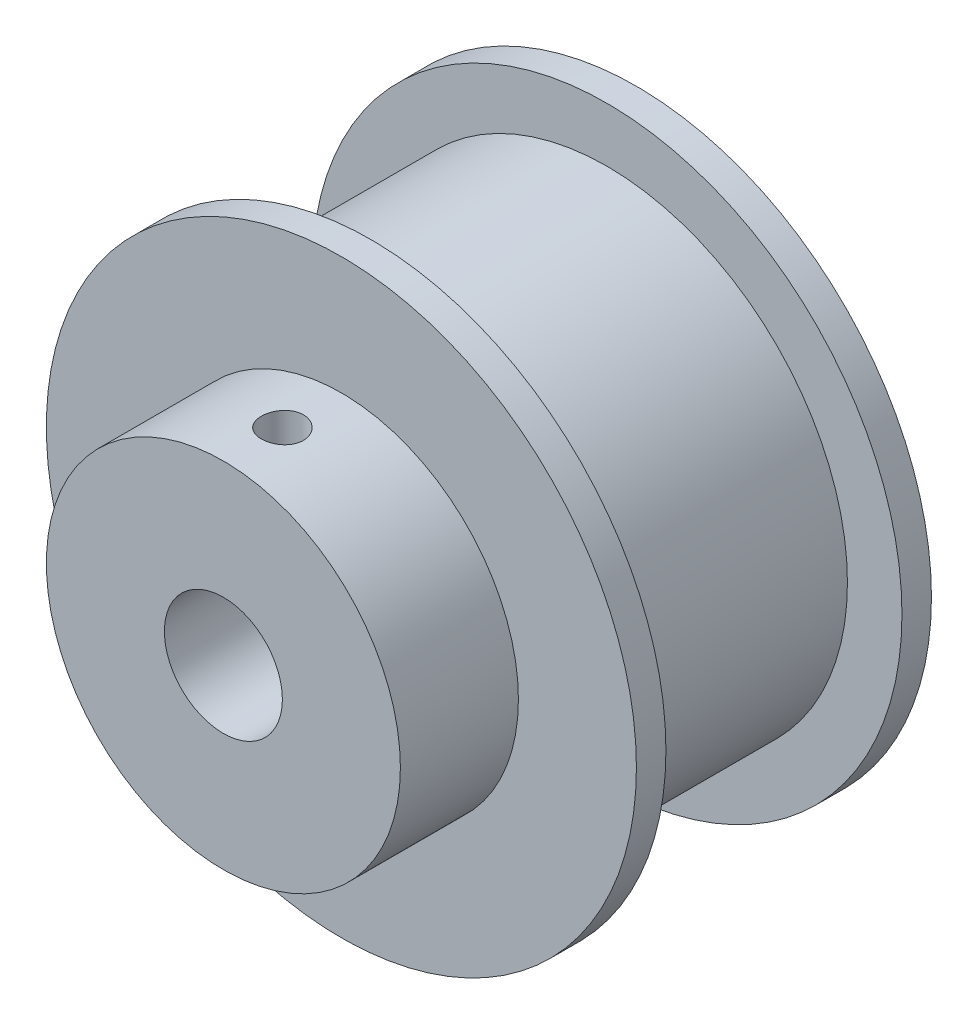
SolidWorks part; units mm, degrees
ref_plane "Front Plane" through (0, 0, 0) normal (0, 0, 1) x (1, 0, 0)
ref_plane "Top Plane" through (0, 0, 0) normal (0, 1, 0) x (1, 0, 0)
ref_plane "Right Plane" through (0, 0, 0) normal (1, 0, 0) x (0, 0, -1)
sketch "Sketch2" plane through (0, 0, 0) normal (1, 0, 0) x (0, 0, -1)
  line L0 (0, 9.525) -> (0, 3.175)
  line L1 (0, 9.525) -> (6.35, 9.525)
  line L2 (6.35, 9.525) -> (6.35, 15.875)
  line L3 (6.35, 15.875) -> (7.9375, 15.875)
  line L4 (7.9375, 15.875) -> (7.9375, 12.9413)
  line L5 (7.9375, 12.9413) -> (20.6375, 12.9413)
  line L6 (20.6375, 12.9413) -> (20.6375, 15.875)
  line L7 (20.6375, 15.875) -> (22.225, 15.875)
  line L8 (22.225, 15.875) -> (22.225, 3.175)
  line L9 (0, 3.175) -> (22.225, 3.175)
  line L10 (0, 0) -> (40.3907, 0) construction
  dimension "D1" = 3.175
  dimension "D2" = 9.525
  dimension "D3" = 12.9413
  dimension "D4" = 12.7
  dimension "D5" = 15.875
  dimension "D6" = 22.225
  dimension "D7" = 15.875
revolve "Revolve1" add sketch "Sketch2" angle 360 about L10
hole_wizard "#4-40 Tapped Hole1" positions "Sketch4" profile "Sketch3" tap size "#4-40" standard "ANSI Inch"
sketch "Sketch4" plane through (0, 0, -22.225) normal (0, 0, -1) x (-1, 0, 0)
  line L1 (0, 0) -> (0, 7.9375) construction
  point P2 (0, 7.9375)
  point P14 (6.8741, 3.9688)
  point P15 (6.8741, -3.9687)
  point P16 (0, -7.9375)
  point P17 (-6.8741, -3.9688)
  point P18 (-6.8741, 3.9687)
  dimension "D1" = 7.9375
  dimension "D2" = 6
sketch "Sketch3" plane through (0, 7.9375, -22.225) normal (1, 0, 0) x (0, 1, 0)
  line L0 (0, 0) -> (0, 9.5692)
  line L1 (0, 9.5692) -> (1.1303, 8.89)
  line L2 (1.1303, 8.89) -> (1.1303, 0)
  line L5 (1.1303, 0) -> (0, 0)
  line L10 (0, 9.5692) -> (-1.1303, 8.89) construction
  line L11 (0, -6.35) -> (0, 107.95) construction
  dimension "Tap Drill Dia." = 2.2606
  dimension "Tap Drill Depth" = 8.89
  dimension "Drill Angle" = 118
cosmetic thread "Hole Thread1"
cosmetic thread "Hole Thread2"
cosmetic thread "Hole Thread3"
cosmetic thread "Hole Thread4"
cosmetic thread "Hole Thread5"
cosmetic thread "Hole Thread6"
sketch "Sketch5" plane through (0, 0, 0) normal (0, 0, 1) x (1, 0, 0)
  line L0 (0, 0) -> (0, 9.525) construction
  circle A0 centre (0, 0) radius 9.525 construction
ref_plane "Plane1" through (0, 9.525, 0) normal (0, 1, 0) x (1, 0, 0)
sketch "Sketch8" plane through (0, 0, -6.35) normal (0, 0, 1) x (1, 0, 0)
  line L0 (0, 9.525) -> (0, 0) construction
  circle A0 centre (0, 0) radius 9.525 construction
hole_wizard "Some set screw. Unknown size" positions "Sketch10" profile "Sketch11" tap size "#4-40" standard "ANSI Inch"
sketch "Sketch10" plane through (0, 9.525, 0) normal (0, 1, 0) x (1, 0, 0)
  line L0 (0, 0) -> (0, 6.35) construction
  point P6 (0, 3.175)
sketch "Sketch11" plane through (0, 9.525, -3.175) normal (1, 0, 0) x (0, 0, 1)
  line L0 (0, 0) -> (0, 6.35)
  line L1 (0, 6.35) -> (1.1303, 6.35)
  line L2 (1.1303, 6.35) -> (1.1303, 0)
  line L5 (1.1303, 0) -> (0, 0)
  line L11 (0, -6.35) -> (0, 107.95) construction
  dimension "Thru Tap Drill Dia." = 2.2606
  dimension "Thru Tap Drill Depth" = 6.35
cosmetic thread "Hole Thread7"
